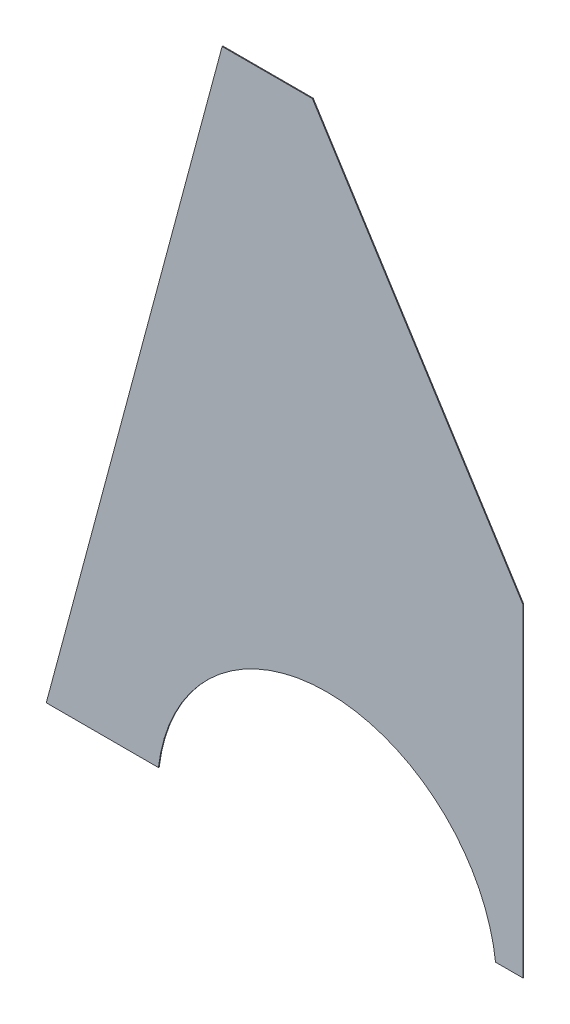
SolidWorks part; units mm, degrees
ref_plane "Front Plane" through (0, 0, 0) normal (0, 0, 1) x (1, 0, 0)
ref_plane "Top Plane" through (0, 0, 0) normal (0, 1, 0) x (1, 0, 0)
ref_plane "Right Plane" through (0, 0, 0) normal (1, 0, 0) x (0, 0, -1)
sketch "Sketch1" plane through (0, 0, 0) normal (0, 0, 1) x (1, 0, 0)
  line L0 (100.415, 808.4507) -> (265.415, 808.4507)
  line L1 (265.415, 808.4507) -> (650.2361, 199.9174)
  line L3 (-221.0383, -391.2292) -> (100.415, 808.4507)
  line L4 (-221.0383, -391.2292) -> (-16.0383, -391.2292)
  line L5 (650.2361, 199.9174) -> (650.2361, -391.2292)
  line L6 (650.2361, -391.2292) -> (600.2361, -391.2292)
  arc A0 (-16.0383, -391.2292) -> (600.2361, -391.2292) centre (292.0989, -427.8024) cw
  dimension "D1" = 165
  dimension "D2" = 720
  dimension "D3" = 75
  dimension "D4" = 1242
  dimension "D5" = 205
  dimension "D6" = 50
extrude "Boss-Extrude1" add sketch "Sketch1" along normal blind 1.5
